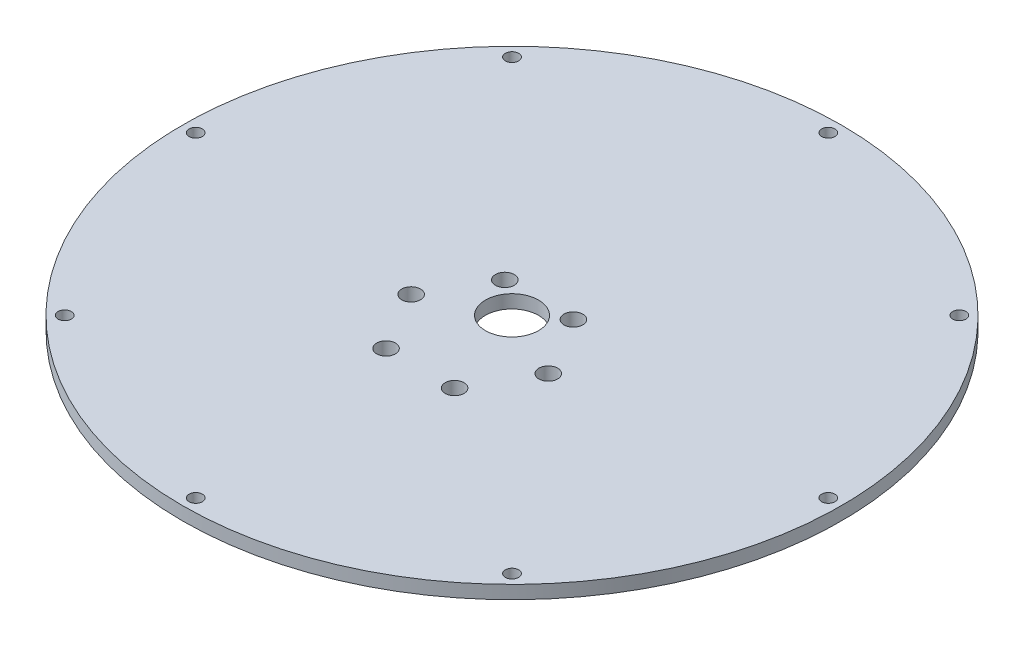
SolidWorks part; units mm, degrees
ref_plane "前视基准面" through (0, 0, 0) normal (0, 0, 1) x (1, 0, 0)
ref_plane "上视基准面" through (0, 0, 0) normal (0, 1, 0) x (1, 0, 0)
ref_plane "右视基准面" through (0, 0, 0) normal (1, 0, 0) x (0, 0, -1)
other "Configuration Table"
sketch "草图2" plane through (0, 0, 0) normal (0, 1, 0) x (1, 0, 0)
  circle A0 centre (0, 0) radius 74.5
  circle A2 centre (0, 71.5) radius 1.5
  circle A3 centre (50.5581, 50.5581) radius 1.5
  circle A4 centre (71.5, 0) radius 1.5
  circle A5 centre (50.5581, -50.5581) radius 1.5
  circle A6 centre (0, -71.5) radius 1.5
  circle A7 centre (-50.5581, -50.5581) radius 1.5
  circle A8 centre (-71.5, 0) radius 1.5
  circle A9 centre (-50.5581, 50.5581) radius 1.5
  circle A10 centre (15.5, -7.3) radius 2.125
  circle A11 centre (0, -7.3) radius 18.3
  circle A12 centre (0, 0) radius 6
  circle A13 centre (7.75, -20.7234) radius 2.125
  circle A14 centre (0, -7.3) radius 18.3
  circle A15 centre (-7.75, -20.7234) radius 2.125
  circle A16 centre (0, -7.3) radius 18.3
  circle A17 centre (-15.5, -7.3) radius 2.125
  circle A18 centre (0, -7.3) radius 18.3
  circle A19 centre (-7.75, 6.1234) radius 2.125
  circle A20 centre (0, -7.3) radius 18.3
  circle A21 centre (7.75, 6.1234) radius 2.125
  circle A22 centre (0, -7.3) radius 18.3
  point P22 (0, 0)
  point P43 (0, -7.3)
  dimension "D1" = 149
  dimension "D2" = 3
  dimension "D5" = 4.25
  dimension "D7" = 36.6
  dimension "D8" = 12
  dimension "D3" = 71.5
  dimension "D6" = 15.5
  dimension "D9" = 7.3
  dimension "D4" = 8
  dimension "D10" = 6
extrude "凸台-拉伸1" add sketch "草图2" along normal blind 3 contours A0 A11 A9 A8 A7 A6 A5 A4 A3 A2 | A11 A21 A19 A17 A15 A13 A12 A10
